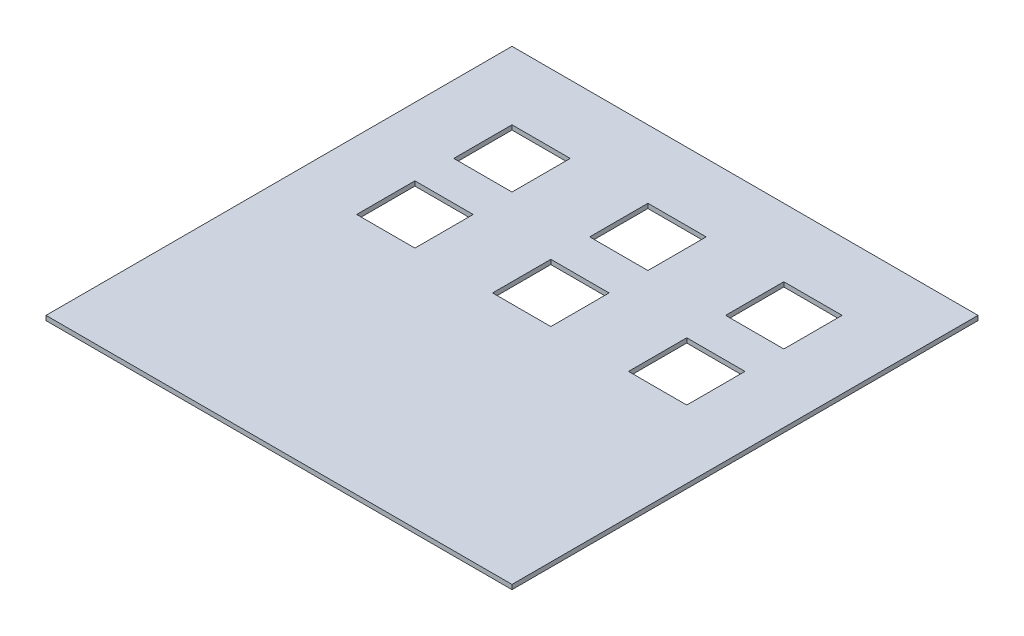
SolidWorks part; units mm, degrees
ref_plane "Front Plane" through (0, 0, 0) normal (0, 0, 1) x (1, 0, 0)
ref_plane "Top Plane" through (0, 0, 0) normal (0, 1, 0) x (1, 0, 0)
ref_plane "Right Plane" through (0, 0, 0) normal (1, 0, 0) x (0, 0, -1)
sketch "Sketch1" plane through (0, 0, 0) normal (0, 1, 0) x (1, 0, 0)
  line L1 (-152.4, -152.4) -> (152.4, -152.4)
  line L2 (-152.4, -152.4) -> (-152.4, 152.4)
  line L3 (-152.4, 152.4) -> (152.4, 152.4)
  line L4 (152.4, -152.4) -> (152.4, 152.4)
  line L5 (-152.4, -152.4) -> (152.4, 152.4) construction
  line L6 (-152.4, 152.4) -> (152.4, -152.4) construction
  point P0 (0, 0)
  dimension "D1" = 304.8
  dimension "D2" = 304.8
extrude "Boss-Extrude1" add sketch "Sketch1" along normal blind 2.9972
sketch "Sketch2" plane through (0, 2.9972, 0) normal (0, 1, 0) x (1, 0, 0)
  line L0 (152.4, 152.4) -> (-152.4, 152.4) construction
  line L1 (-107.95, 69.85) -> (-69.85, 69.85)
  line L2 (-107.95, 69.85) -> (-107.95, 107.95)
  line L3 (-107.95, 107.95) -> (-69.85, 107.95)
  line L4 (-69.85, 69.85) -> (-69.85, 107.95)
  line L5 (-107.95, 69.85) -> (-69.85, 107.95) construction
  line L6 (-107.95, 107.95) -> (-69.85, 69.85) construction
  line L7 (-152.4, 152.4) -> (-152.4, -152.4) construction
  point P0 (-88.9, 88.9)
  dimension "D1" = 38.1
  dimension "D2" = 38.1
  dimension "D3" = 44.45
  dimension "D4" = 44.45
extrude "Cut-Extrude1" cut sketch "Sketch2" against normal blind 2.9972
pattern_linear "LPattern1" count 3 spacing 88.9 along (1, 0, 0) count 2 spacing 63.5 along (0, 0, 1) of "Cut-Extrude1"
